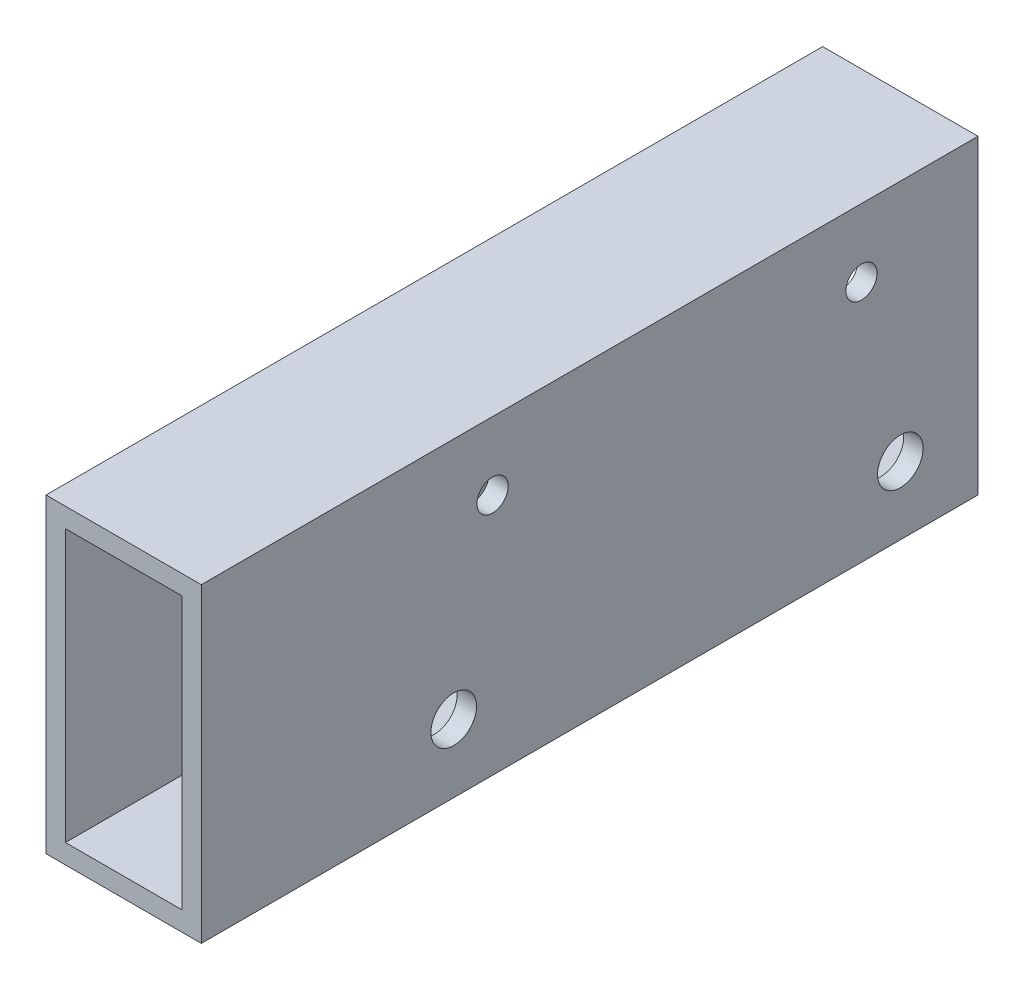
SolidWorks part; units mm, degrees
material "6061-T4 (SS)"
ref_plane "Front Plane" through (0, 0, 0) normal (0, 0, 1) x (1, 0, 0)
ref_plane "Top Plane" through (0, 0, 0) normal (0, 1, 0) x (1, 0, 0)
ref_plane "Right Plane" through (0, 0, 0) normal (1, 0, 0) x (0, 0, -1)
sketch "Sketch1" plane through (0, 0, 0) normal (0, 0, 1) x (1, 0, 0)
  line L0 (-9.525, 22.225) -> (9.525, 22.225)
  line L1 (-12.7, 25.4) -> (12.7, 25.4)
  line L2 (-12.7, 25.4) -> (-12.7, -25.4)
  line L3 (-12.7, -25.4) -> (12.7, -25.4)
  line L4 (12.7, 25.4) -> (12.7, -25.4)
  line L5 (-12.7, 25.4) -> (12.7, -25.4) construction
  line L6 (-12.7, -25.4) -> (12.7, 25.4) construction
  line L7 (9.525, 22.225) -> (9.525, -22.225)
  line L8 (-9.525, -22.225) -> (9.525, -22.225)
  line L9 (-9.525, 22.225) -> (-9.525, -22.225)
  point P0 (0, 0)
  dimension "D1" = 50.8
  dimension "D2" = 25.4
  dimension "D3" = 3.175
extrude "Boss-Extrude1" add sketch "Sketch1" along normal mid plane 127
sketch "Sketch3" plane through (12.7, 0, 0) normal (1, 0, 0) x (0, 0, -1)
  line L0 (-63.5, 0) -> (63.5, 0) construction
  line L1 (-63.5, -25.4) -> (-63.5, 25.4) construction
  line L2 (63.5, -25.4) -> (63.5, 25.4) construction
  line L3 (50.8, 14.2875) -> (50.8, -14.2875) construction
  line L4 (50.8, -14.2875) -> (-63.5, -14.2875) construction
  line L5 (50.8, 14.2875) -> (44.45, 14.2875) construction
  line L6 (44.45, 14.2875) -> (-15.875, 14.2875) construction
  line L7 (-63.5, -25.4) -> (63.5, -25.4) construction
  circle A0 centre (50.8, -14.2875) radius 3.7287
  circle A1 centre (-22.225, -14.2875) radius 3.7287
  circle A2 centre (44.45, 14.2875) radius 2.5527
  circle A3 centre (-15.875, 14.2875) radius 2.5527
  point P9 (50.8, 0)
  dimension "D3" = 7.4574
  dimension "D5" = 6.35
  dimension "D6" = 5.1054
  dimension "D1" = 28.575
  dimension "D2" = 12.7
  dimension "D4" = 73.025
  dimension "D7" = 60.325
extrude "Cut-Extrude1" cut sketch "Sketch3" against normal through all
